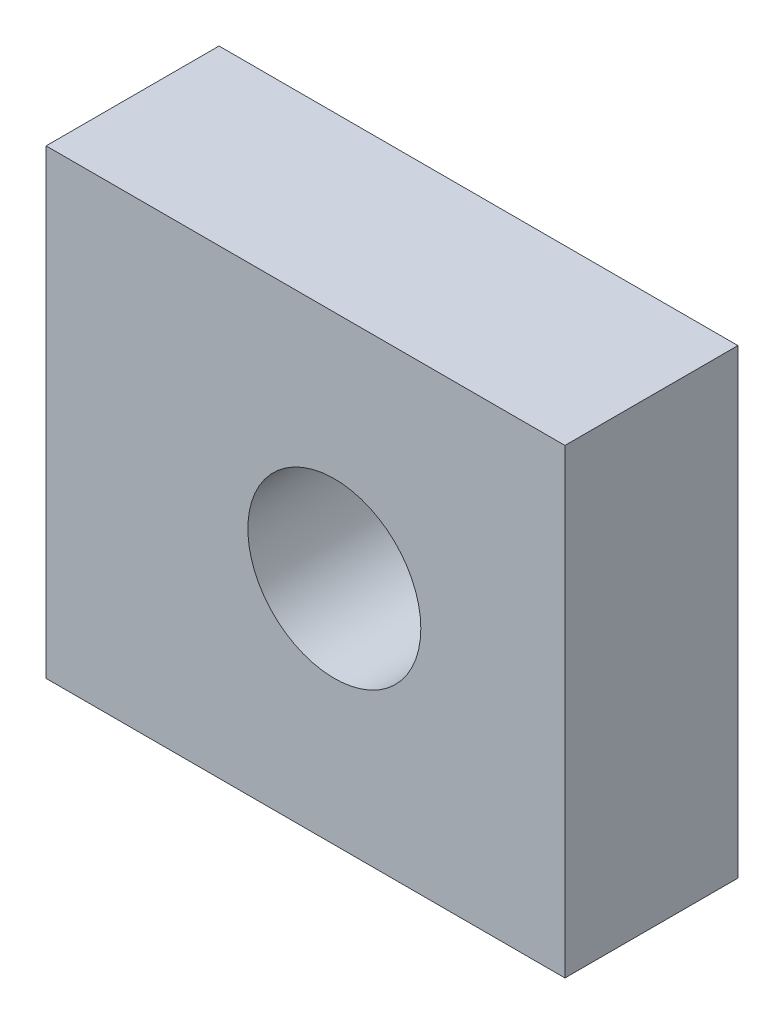
SolidWorks part; units mm, degrees
ref_plane "Спереди" through (0, 0, 0) normal (0, 0, 1) x (1, 0, 0)
ref_plane "Сверху" through (0, 0, 0) normal (0, 1, 0) x (1, 0, 0)
ref_plane "Справа" through (0, 0, 0) normal (1, 0, 0) x (0, 0, -1)
other "Configuration Table"
sketch "Эскиз1" plane through (0, 0, 0) normal (0, 0, 1) x (1, 0, 0)
  line L0 (4.5, 8) -> (4.5, 0) construction
  line L1 (0, 0) -> (9, 0)
  line L2 (0, 0) -> (0, 8)
  line L3 (0, 8) -> (9, 8)
  line L4 (9, 0) -> (9, 8)
  line L5 (0, 4) -> (9, 4) construction
  dimension "D1" = 9
  dimension "D2" = 8
extrude "Бобышка-Вытянуть1" add sketch "Эскиз1" along normal blind 3
sketch "Эскиз2" plane through (0, 0, 3) normal (0, 0, 1) x (1, 0, 0)
  line L0 (0, 0) -> (9, 0) construction
  line L1 (0, 8) -> (0, 0) construction
  circle A0 centre (5, 4) radius 1.5
  dimension "D1" = 3
  dimension "D2" = 4
  dimension "D3" = 5
extrude "Вырез-Вытянуть1" cut sketch "Эскиз2" against normal through all
